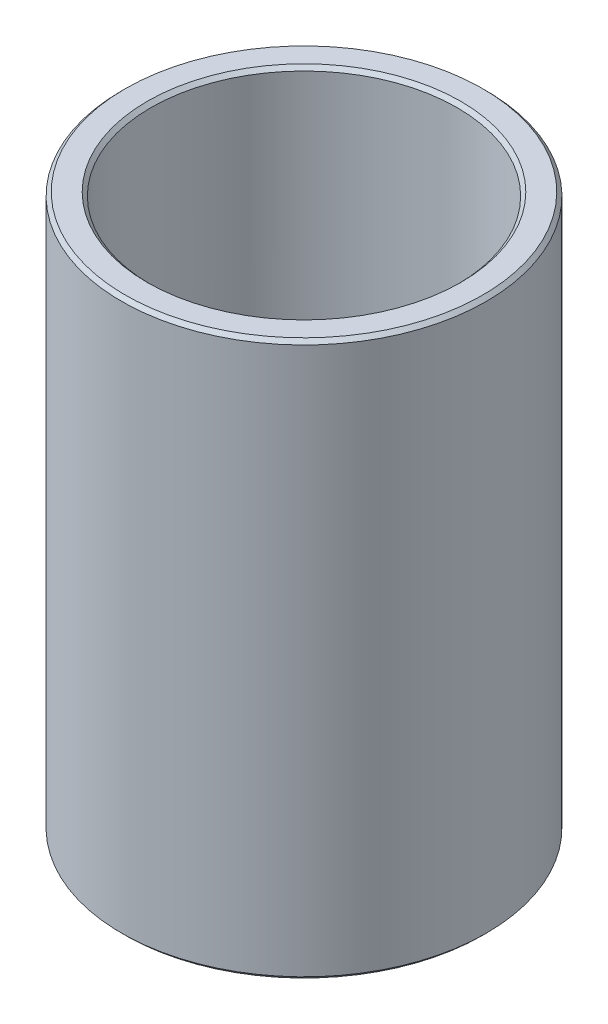
SolidWorks part; units mm, degrees
material "Brass"
ref_plane "Front Plane" through (0, 0, 0) normal (0, 0, 1) x (1, 0, 0)
ref_plane "Top Plane" through (0, 0, 0) normal (0, 1, 0) x (1, 0, 0)
ref_plane "Right Plane" through (0, 0, 0) normal (1, 0, 0) x (0, 0, -1)
sketch "Sketch1" plane through (0, 0, 0) normal (0, 0, 1) x (1, 0, 0)
  line L0 (0, -587.1511) -> (0, 28770.4063) construction
  line L1 (2, 0) -> (2, 1)
  line L2 (2, 1) -> (5, 4)
  line L3 (5, 4) -> (10.5, 4)
  line L4 (10.5, 4) -> (10.5, 38)
  line L5 (10.5, 38) -> (12.5, 38)
  line L6 (12.5, 38) -> (12.5, 0)
  line L7 (12.5, 0) -> (2, 0)
  dimension "D1" = 25
  dimension "D2" = 38
  dimension "D3" = 2
  dimension "D4" = 4
  dimension "D5" = 4
  dimension "D6" = 45
  dimension "D7" = 10
revolve "Revolve1" add sketch "Sketch1" angle 360 about L0
chamfer "Chamfer1" distance 0.25 angle 45 4 edges at (12.5, 38, 0) (10.5, 38, 0) (12.5, 0, 0) (2, 0, 0)
